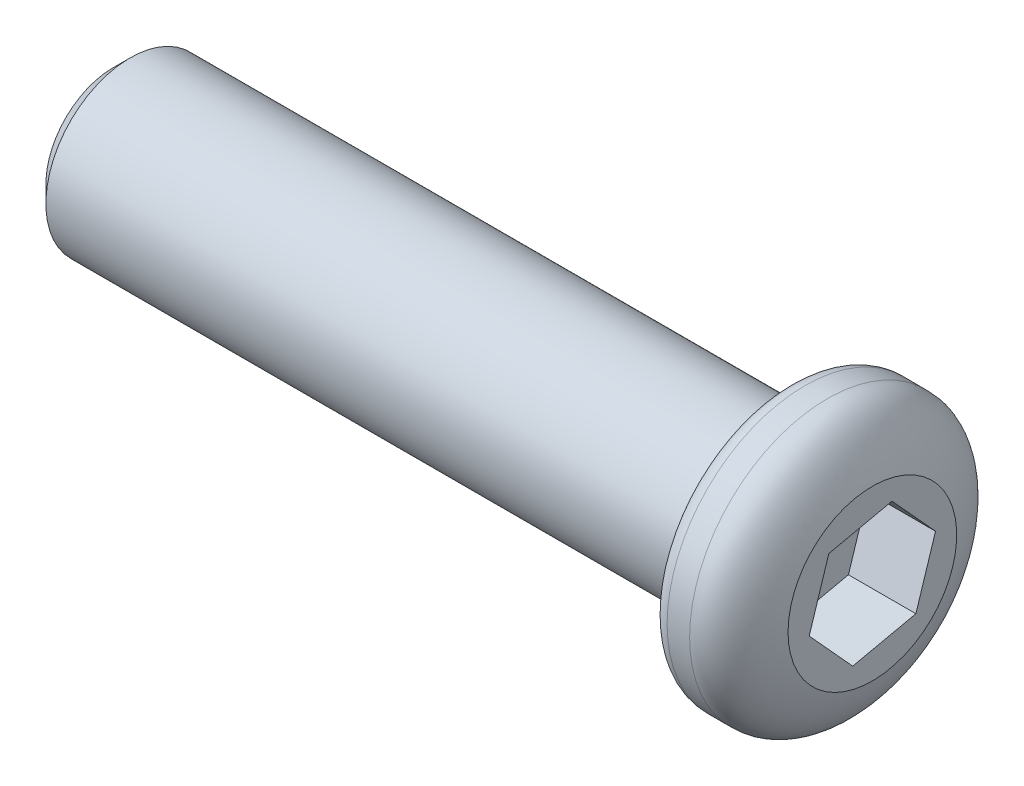
SolidWorks part; units mm, degrees
ref_plane "Front Plane" through (0, 0, 0) normal (0, 0, 1) x (1, 0, 0)
ref_plane "Top Plane" through (0, 0, 0) normal (0, 1, 0) x (1, 0, 0)
ref_plane "Right Plane" through (0, 0, 0) normal (1, 0, 0) x (0, 0, -1)
sketch "Sketch1" plane through (0, 0, 0) normal (0, 1, 0) x (1, 0, 0)
  line L0 (-60.711, 0) -> (110.8635, 0) construction
  line L1 (0, 0) -> (0, 1.5)
  line L2 (0, 1.5) -> (12, 1.5)
  line L3 (12, 1.5) -> (12, 2.45)
  line L4 (12, 2.45) -> (12.7, 2.45)
  line L5 (13.5, 1.5) -> (13.5, 0)
  line L6 (0, 0) -> (13.5, 0)
  spline S0 degree 2 poles (12.7, 2.45) (13.1904, 2.4846) (13.5, 1.5) knots 0 0 0 0.61502 0.61502 0.61502
  dimension "D6" = 1.5
  dimension "D1" = 12
  dimension "D2" = 1.5
  dimension "D3" = 2.45
  dimension "D4" = 0.7
  dimension "D5" = 1.5
revolve "Revolve1" add sketch "Sketch1" angle 360 about L0
sketch "Sketch2" plane through (13.5, 0, 0) normal (1, 0, 0) x (0, 0, -1)
  line L1 (0.3493, 1.0957) -> (-0.7742, 0.8503)
  line L2 (-0.7742, 0.8503) -> (-1.1235, -0.2453)
  line L3 (-1.1235, -0.2453) -> (-0.3493, -1.0957)
  line L4 (-0.3493, -1.0957) -> (0.7742, -0.8503)
  line L5 (0.7742, -0.8503) -> (1.1235, 0.2453)
  line L6 (1.1235, 0.2453) -> (0.3493, 1.0957)
  circle A0 centre (0, 0) radius 0.9959 construction
  dimension "D1" = 2.3
extrude "Cut-Extrude1" cut sketch "Sketch2" against normal blind 1.2
chamfer "Chamfer1" distance 0.3 angle 45 2 edges at (12, 0, 1.5) (0, 0, 1.5)
fillet "Fillet1" radius 0.3 1 edges at (12, 0, 2.45)
